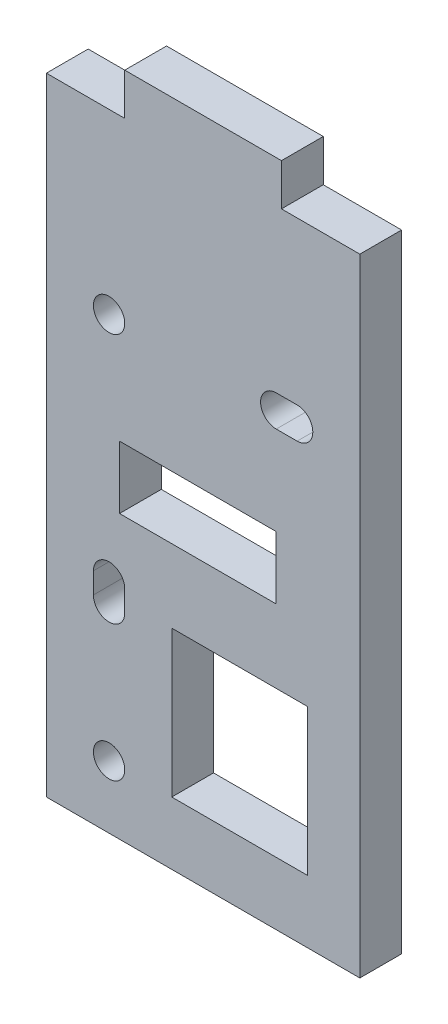
SolidWorks part; units mm, degrees
ref_plane "Front Plane" through (0, 0, 0) normal (0, 0, 1) x (1, 0, 0)
ref_plane "Top Plane" through (0, 0, 0) normal (0, 1, 0) x (1, 0, 0)
ref_plane "Right Plane" through (0, 0, 0) normal (1, 0, 0) x (0, 0, -1)
sketch "Sketch1" plane through (0, 0, 0) normal (0, 0, 1) x (1, 0, 0)
  line L0 (6, 0) -> (6, 60) construction
  line L1 (0, 0) -> (30, 0)
  line L2 (0, 0) -> (0, 60)
  line L3 (0, 60) -> (7.5, 60)
  line L4 (30, 0) -> (30, 60)
  line L6 (7.5, 60) -> (7.5, 64)
  line L7 (7.5, 64) -> (22.5, 64)
  line L8 (22.5, 60) -> (22.5, 64)
  line L9 (12, 20) -> (25, 20)
  line L10 (12, 20) -> (12, 6)
  line L11 (12, 6) -> (25, 6)
  line L12 (25, 20) -> (25, 6)
  line L13 (0, 43) -> (30, 43) construction
  line L14 (22.5, 60) -> (30, 60)
  line L15 (7, 33) -> (22, 33)
  line L16 (7, 33) -> (7, 27)
  line L17 (7, 27) -> (22, 27)
  line L18 (22, 33) -> (22, 27)
  line L19 (6, 21) -> (6, 19) construction
  line L20 (7.5, 21) -> (7.5, 19)
  line L21 (4.5, 21) -> (4.5, 19)
  line L22 (22, 43) -> (24, 43) construction
  line L23 (22, 44.5) -> (24, 44.5)
  line L24 (22, 41.5) -> (24, 41.5)
  circle A1 centre (6, 6) radius 1.5
  circle A2 centre (6, 43) radius 1.5
  arc A4 (7.5, 21) -> (4.5, 21) centre (6, 21) ccw
  arc A5 (4.5, 19) -> (7.5, 19) centre (6, 19) ccw
  arc A6 (22, 44.5) -> (22, 41.5) centre (22, 43) ccw
  arc A7 (24, 41.5) -> (24, 44.5) centre (24, 43) ccw
  point P31 (6, 20)
  point P36 (23, 43)
  dimension "D11" = 1
  dimension "D12" = 3
  dimension "D16" = 2
  dimension "D17" = 3
  dimension "D21" = 0
  dimension "D10" = 17
  dimension "D18" = 6
  dimension "D1" = 60
  dimension "D2" = 30
  dimension "D3" = 15
  dimension "D4" = 7.5
  dimension "D5" = 4
  dimension "D6" = 6
  dimension "D7" = 13
  dimension "D8" = 14
  dimension "D9" = 6
  dimension "D13" = 6
  dimension "D14" = 1
  dimension "D15" = 6
  dimension "D19" = 10
  dimension "D20" = 0
extrude "Boss-Extrude1" add sketch "Sketch1" along normal blind 4
